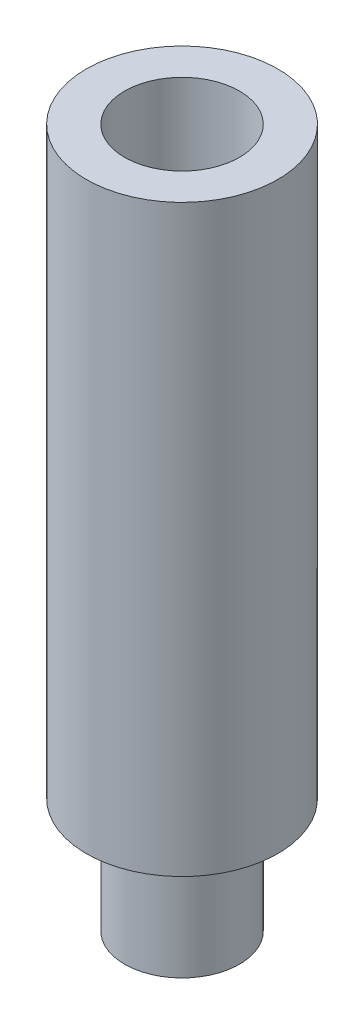
SolidWorks part; units mm, degrees
ref_plane "Front Plane" through (0, 0, 0) normal (0, 0, 1) x (1, 0, 0)
ref_plane "Top Plane" through (0, 0, 0) normal (0, 1, 0) x (1, 0, 0)
ref_plane "Right Plane" through (0, 0, 0) normal (1, 0, 0) x (0, 0, -1)
sketch "Sketch1" plane through (0, 0, 0) normal (0, 0, 1) x (1, 0, 0)
  line L0 (-2.5, 18.24) -> (-2.5, 3)
  line L1 (-2.5, 3) -> (-1.5, 3)
  line L2 (-1.5, 3) -> (-1.5, 0)
  line L3 (-1.5, 0) -> (0, 0)
  line L4 (-2.5, 18.24) -> (-1.5, 18.24)
  line L5 (-1.5, 18.24) -> (-1.5, 13.24)
  line L6 (-1.5, 13.24) -> (0, 13.24)
  line L7 (0, 13.24) -> (0, 0)
  line L8 (0, 38.3835) -> (0, 10.8001) construction
  dimension "D1" = 15.24
  dimension "D2" = 1.5
  dimension "D3" = 2.5
  dimension "D4" = 5
  dimension "D5" = 3
revolve "Revolve1" add sketch "Sketch1" angle 360 about L8
